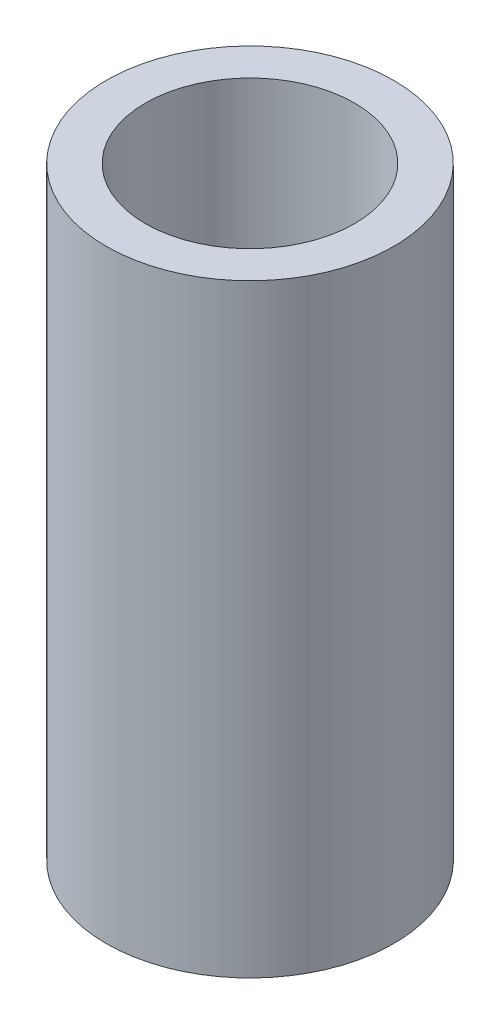
SolidWorks part; units mm, degrees
ref_plane "Front Plane" through (0, 0, 0) normal (0, 0, 1) x (1, 0, 0)
ref_plane "Top Plane" through (0, 0, 0) normal (0, 1, 0) x (1, 0, 0)
ref_plane "Right Plane" through (0, 0, 0) normal (1, 0, 0) x (0, 0, -1)
sketch "Sketch1" plane through (0, 0, 0) normal (0, 1, 0) x (1, 0, 0)
  circle A0 centre (0, 0) radius 4
  circle A1 centre (0, 0) radius 5.5
  dimension "D1" = 8
  dimension "D2" = 11
extrude "Boss-Extrude1" add sketch "Sketch1" along normal blind 23.1
